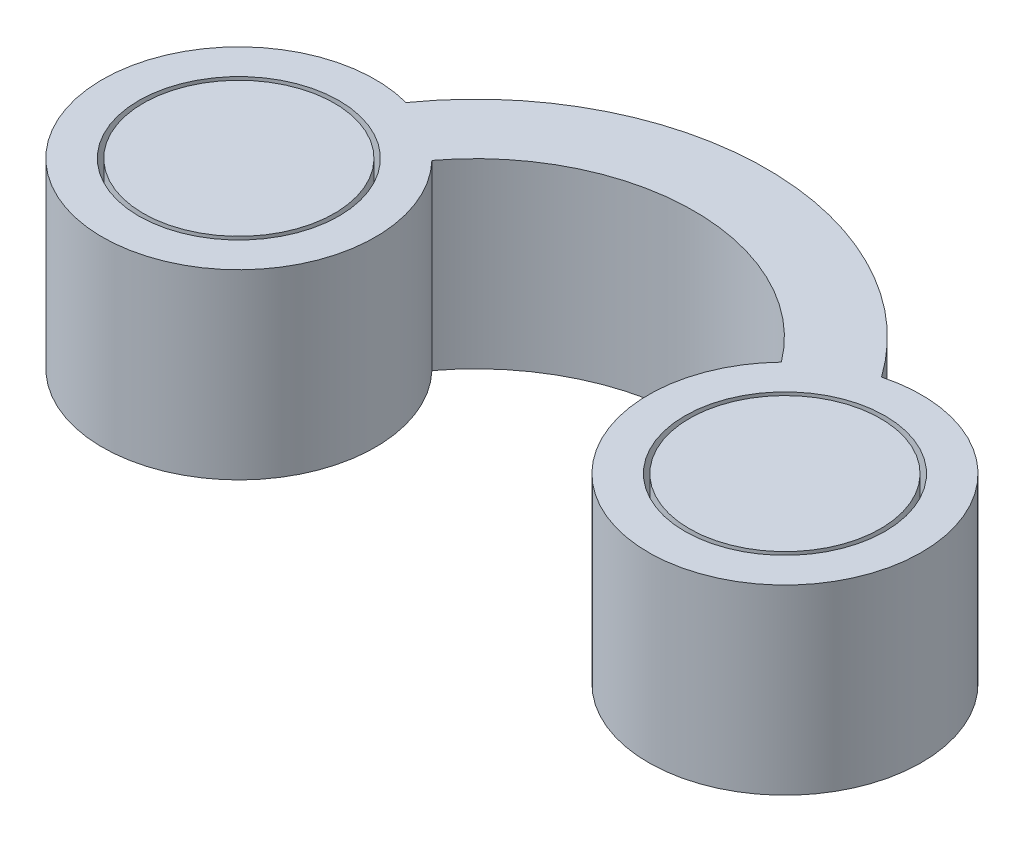
SolidWorks part; units mm, degrees
ref_plane "前视基准面" through (0, 0, 0) normal (0, 0, 1) x (1, 0, 0)
ref_plane "上视基准面" through (0, 0, 0) normal (0, 1, 0) x (1, 0, 0)
ref_plane "右视基准面" through (0, 0, 0) normal (1, 0, 0) x (0, 0, -1)
sketch "草图1" plane through (0, 0, 0) normal (0, 1, 0) x (1, 0, 0)
  line L0 (0, -5.9315) -> (0, 5.9315) construction
  line L1 (-1.5, 0) -> (1.5, 0) construction
  line L2 (-0.7772, 0.2) -> (0.7772, 0.2)
  line L3 (-0.7772, -0.2) -> (0.7772, -0.2)
  circle A0 centre (1.5, 0) radius 0.55
  circle A1 centre (1.5, 0) radius 0.75
  circle A2 centre (-1.5, 0) radius 0.75
  circle A3 centre (-1.5, 0) radius 0.55
  arc A4 (-1.3059, 0.7244) -> (1.3059, 0.7244) centre (0, -0.2) cw
  arc A5 (-0.9598, 0.5203) -> (0.9598, 0.5203) centre (0, -0.2) cw
  point P12 (0, 0)
  point P15 (0, -0.2)
  point P16 (0, 0.2)
  dimension "D1" = 1.5
  dimension "D2" = 1.1
  dimension "D5" = 0.4
  dimension "D6" = 1.2
  dimension "D3" = 3
  dimension "D4" = 0.4
extrude "凸台-拉伸1" add sketch "草图1" along normal mid plane 1 contours A1 A0 | A2 A3 | A2 A5 A1 A4
sketch "草图2" plane through (0, 0, 0) normal (0, 1, 0) x (1, 0, 0)
  circle A1 centre (-1.5, 0) radius 0.525
  circle A2 centre (1.5, 0) radius 0.525
  dimension "D1" = 1.05
  dimension "D2" = 1.05
extrude "凸台-拉伸3" add sketch "草图2" along normal mid plane 1
